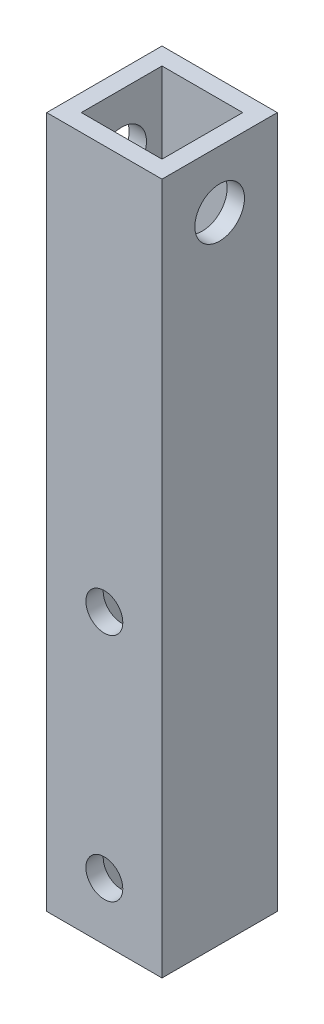
SolidWorks part; units mm, degrees
material "5052-H34"
ref_plane "正面" through (0, 0, 0) normal (0, 0, 1) x (1, 0, 0)
ref_plane "平面" through (0, 0, 0) normal (0, 1, 0) x (1, 0, 0)
ref_plane "右側面" through (0, 0, 0) normal (1, 0, 0) x (0, 0, -1)
sketch "ｽｹｯﾁ1" plane through (0, 0, 0) normal (0, 1, 0) x (1, 0, 0)
  line L1 (-5, 5) -> (5, 5)
  line L2 (-5, 5) -> (-5, -5)
  line L3 (-5, -5) -> (5, -5)
  line L4 (5, 5) -> (5, -5)
  line L5 (-5, 5) -> (5, -5) construction
  line L6 (-5, -5) -> (5, 5) construction
  point P0 (0, 0)
  dimension "D1" = 10
  dimension "D2" = 10
extrude "押し出し-薄板1" add sketch "ｽｹｯﾁ1" along normal blind 60 thin
sketch "ｽｹｯﾁ2" plane through (0, 0, 5) normal (0, 0, 1) x (1, 0, 0)
  line L0 (0, 0) -> (0, 25) construction
  line L1 (-5, 60) -> (5, 60) construction
  circle A0 centre (0, 25) radius 1.6
  circle A1 centre (0, 5) radius 1.6
  point P6 (0, 15)
  dimension "D1" = 3.2
  dimension "D2" = 10
  dimension "D3" = 20
  dimension "D4" = 45
extrude "ｶｯﾄ - 押し出し1" cut sketch "ｽｹｯﾁ2" against normal through all
sketch "ｽｹｯﾁ3" plane through (5, 0, 0) normal (1, 0, 0) x (0, 0, -1)
  line L0 (0, 60) -> (0, 55) construction
  line L1 (-5, 60) -> (5, 60) construction
  circle A0 centre (0, 55) radius 2.15
  dimension "D2" = 4.3
  dimension "D1" = 5
extrude "ｶｯﾄ - 押し出し2" cut sketch "ｽｹｯﾁ3" against normal through all
